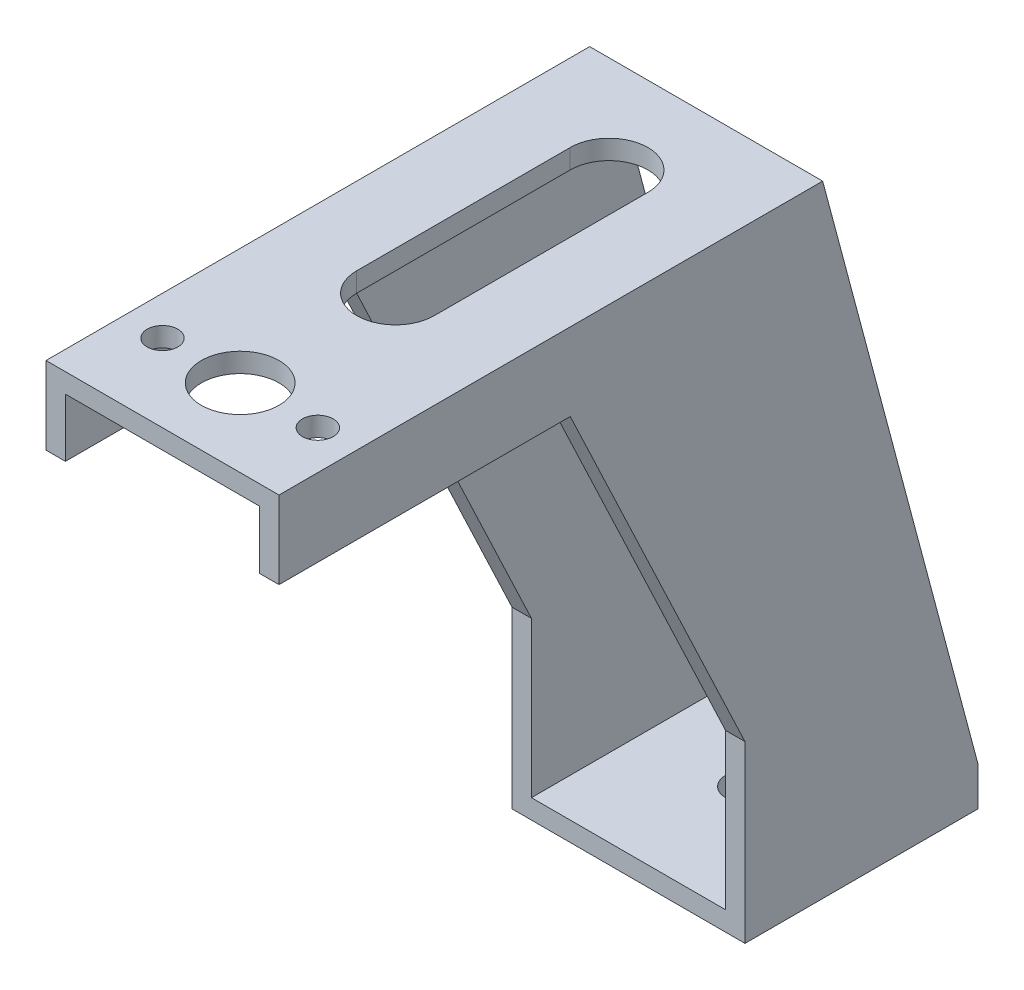
SolidWorks part; units mm, degrees
material "6061-T6 (SS)"
ref_plane "Front Plane" through (0, 0, 0) normal (0, 0, 1) x (1, 0, 0)
ref_plane "Top Plane" through (0, 0, 0) normal (0, 1, 0) x (1, 0, 0)
ref_plane "Right Plane" through (0, 0, 0) normal (1, 0, 0) x (0, 0, -1)
sketch "Sketch3" plane through (0, 0, 0) normal (0, 0, 1) x (1, 0, 0)
  line L0 (3.175, 98.425) -> (34.925, 98.425)
  line L1 (0, 0) -> (38.1, 0)
  line L2 (0, 0) -> (0, 101.6)
  line L3 (0, 101.6) -> (38.1, 101.6)
  line L4 (38.1, 0) -> (38.1, 101.6)
  line L5 (34.925, 3.175) -> (34.925, 98.425)
  line L6 (3.175, 3.175) -> (34.925, 3.175)
  line L7 (3.175, 3.175) -> (3.175, 98.425)
  dimension "D1" = 38.1
  dimension "D2" = 3.175
  dimension "D3" = 101.6
extrude "Boss-Extrude1" add sketch "Sketch3" along normal blind 114.3
sketch "Sketch5" plane through (0, 0, 0) normal (-1, 0, 0) x (0, 0, 1)
  line L0 (0, 6.35) -> (25.4, 101.6)
  line L1 (38.1, 28.575) -> (66.675, 88.9)
  line L2 (114.3, 101.6) -> (0, 101.6) construction
  line L4 (0, 6.35) -> (0, 101.6)
  line L5 (0, 101.6) -> (25.4, 101.6)
  line L6 (38.1, 0) -> (38.1, 88.9)
  line L7 (114.3, 0) -> (0, 0) construction
  line L8 (38.1, 88.9) -> (114.3, 88.9)
  line L9 (114.3, 101.6) -> (114.3, 0) construction
  line L10 (114.3, 88.9) -> (114.3, 0)
  line L11 (114.3, 0) -> (38.1, 0)
  line L12 (0, 101.6) -> (0, 0) construction
  dimension "D1" = 12.7
  dimension "D2" = 38.1
  dimension "D3" = 25.4
  dimension "D4" = 3.175
  dimension "D5" = 28.575
  dimension "D6" = 28.575
extrude "Cut-Extrude1" cut sketch "Sketch5" against normal through all
sketch "Sketch6" plane through (0, 0, 0) normal (0, -1, 0) x (1, 0, 0)
  line L4 (6.35, 19.05) -> (31.75, 19.05) construction
  line L8 (31.75, 6.35) -> (31.75, 31.75)
  line L9 (31.75, 31.75) -> (6.35, 31.75)
  line L10 (6.35, 31.75) -> (6.35, 6.35)
  line L11 (6.35, 6.35) -> (31.75, 6.35)
  line L12 (31.75, 6.35) -> (31.75, 31.75) construction
  line L13 (31.75, 31.75) -> (6.35, 31.75) construction
  line L14 (6.35, 31.75) -> (6.35, 6.35) construction
  line L15 (6.35, 6.35) -> (31.75, 6.35) construction
  circle A0 centre (6.35, 31.75) radius 2.4003 construction
  circle A1 centre (31.75, 31.75) radius 2.4003 construction
  circle A2 centre (31.75, 6.35) radius 2.4003
  circle A3 centre (6.35, 6.35) radius 2.4003
  circle A4 centre (19.05, 19.05) radius 3.175
  dimension "D2" = 4.8006
  dimension "D3" = 6.35
  dimension "D1" = 6.35
extrude "Cut-Extrude2" cut sketch "Sketch6" against normal up to next
sketch "Sketch7" plane through (0, 101.6, 0) normal (0, 1, 0) x (1, 0, 0)
  line L2 (19.05, -41.275) -> (19.05, -76.2) construction
  line L3 (25.4, -41.275) -> (25.4, -76.2)
  line L4 (12.7, -41.275) -> (12.7, -76.2)
  line L5 (38.1, -114.3) -> (0, -114.3) construction
  line L6 (38.1, -25.4) -> (0, -25.4) construction
  line L7 (0, -114.3) -> (0, -25.4) construction
  line L8 (38.1, -114.3) -> (38.1, -25.4) construction
  circle A0 centre (6.35, -101.6) radius 2.5146
  arc A1 (25.4, -41.275) -> (12.7, -41.275) centre (19.05, -41.275) ccw
  arc A2 (12.7, -76.2) -> (25.4, -76.2) centre (19.05, -76.2) ccw
  circle A3 centre (31.75, -101.6) radius 2.5146
  circle A4 centre (19.05, -101.6) radius 6.35
  point P2 (19.05, -114.3)
  point P8 (19.05, -58.7375)
  dimension "D1" = 38.1
  dimension "D2" = 6.35
  dimension "D3" = 5.0292
  dimension "D5" = 15.875
  dimension "D6" = 12.7
  dimension "D4" = 6.35
  dimension "D7" = 6.35
  dimension "D8" = 12.7
extrude "Cut-Extrude3" cut sketch "Sketch7" against normal up to next
